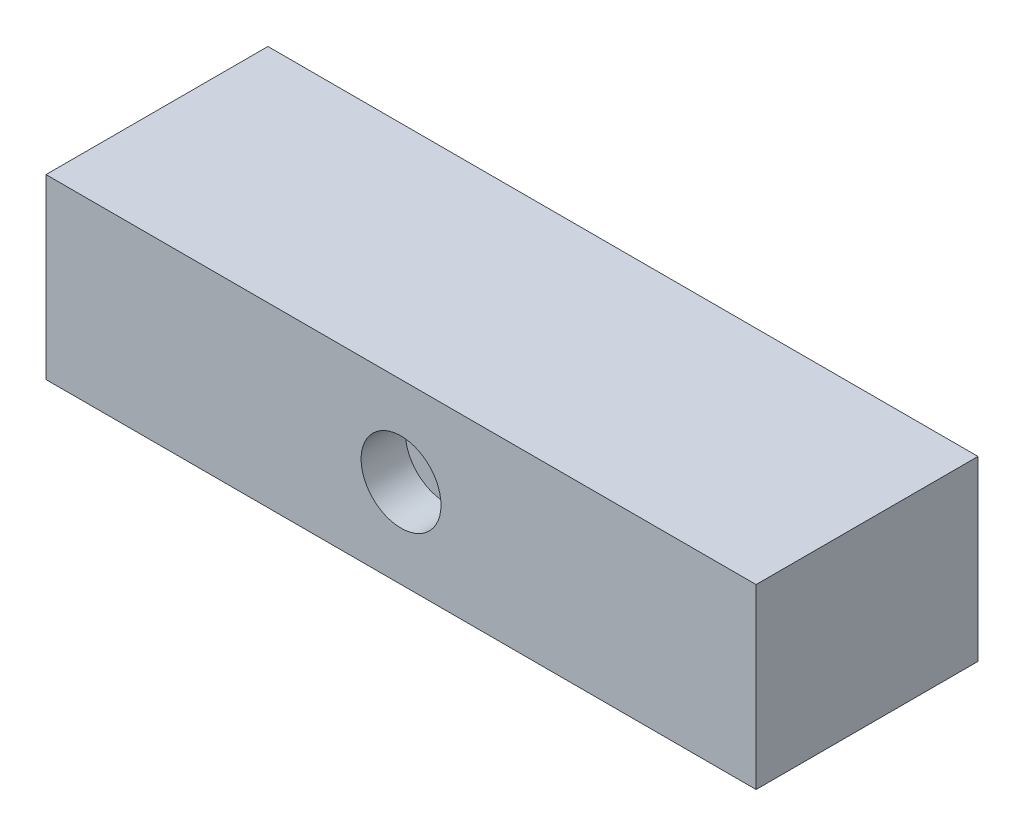
SolidWorks part; units mm, degrees
ref_plane "Front Plane" through (0, 0, 0) normal (0, 0, 1) x (1, 0, 0)
ref_plane "Top Plane" through (0, 0, 0) normal (0, 1, 0) x (1, 0, 0)
ref_plane "Right Plane" through (0, 0, 0) normal (1, 0, 0) x (0, 0, -1)
sketch "Sketch1" plane through (0, 0, 0) normal (0, 0, 1) x (1, 0, 0)
  line L0 (0, 0) -> (-16456.2663, 0) construction
  line L2 (-20, -5) -> (20, -5)
  line L3 (-20, -5) -> (-20, 5)
  line L4 (-20, 5) -> (20, 5)
  line L5 (20, -5) -> (20, 5)
  line L6 (-20, -5) -> (20, 5) construction
  line L7 (-20, 5) -> (20, -5) construction
  point P3 (0, 0)
  dimension "D1" = 40
  dimension "D2" = 10
extrude "Boss-Extrude1" add sketch "Sketch1" along normal blind 12.5 contours L3 L2 L5 L4
sketch "Sketch2" plane through (0, 0, 12.5) normal (0, 0, 1) x (1, 0, 0)
  circle A0 centre (0, 0) radius 2.25
extrude "Cut-Extrude1" cut sketch "Sketch2" against normal blind 2.5
